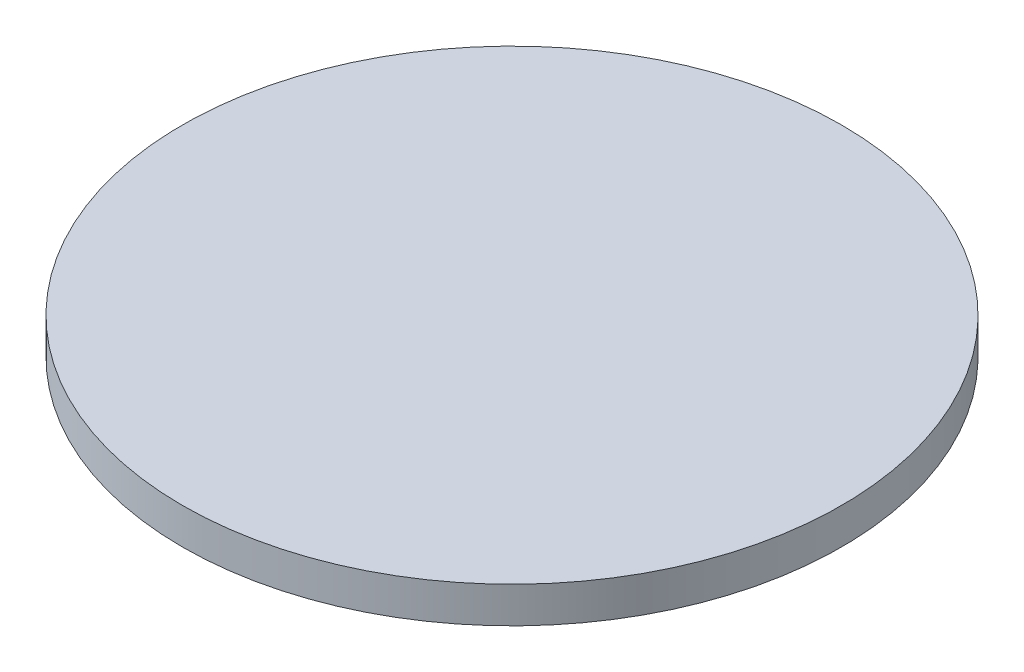
SolidWorks part; units mm, degrees
ref_plane "Plan de face" through (0, 0, 0) normal (0, 0, 1) x (1, 0, 0)
ref_plane "Plan de dessus" through (0, 0, 0) normal (0, 1, 0) x (1, 0, 0)
ref_plane "Plan de droite" through (0, 0, 0) normal (1, 0, 0) x (0, 0, -1)
sketch "Esquisse1" plane through (0, 0, 0) normal (0, 1, 0) x (1, 0, 0)
sketch "Esquisse2" plane through (0, 0, 0) normal (0, 1, 0) x (1, 0, 0)
  circle A0 centre (0, 0) radius 64
  dimension "D1" = 128
extrude "Boss.-Extru.1" add sketch "Esquisse2" along normal blind 7
sketch "Esquisse3" plane through (0, 7, 0) normal (0, 1, 0) x (1, 0, 0)
  circle A0 centre (0, 0) radius 37.5
  circle A1 centre (0, 0) radius 32.5
  dimension "D1" = 75
  dimension "D2" = 5
